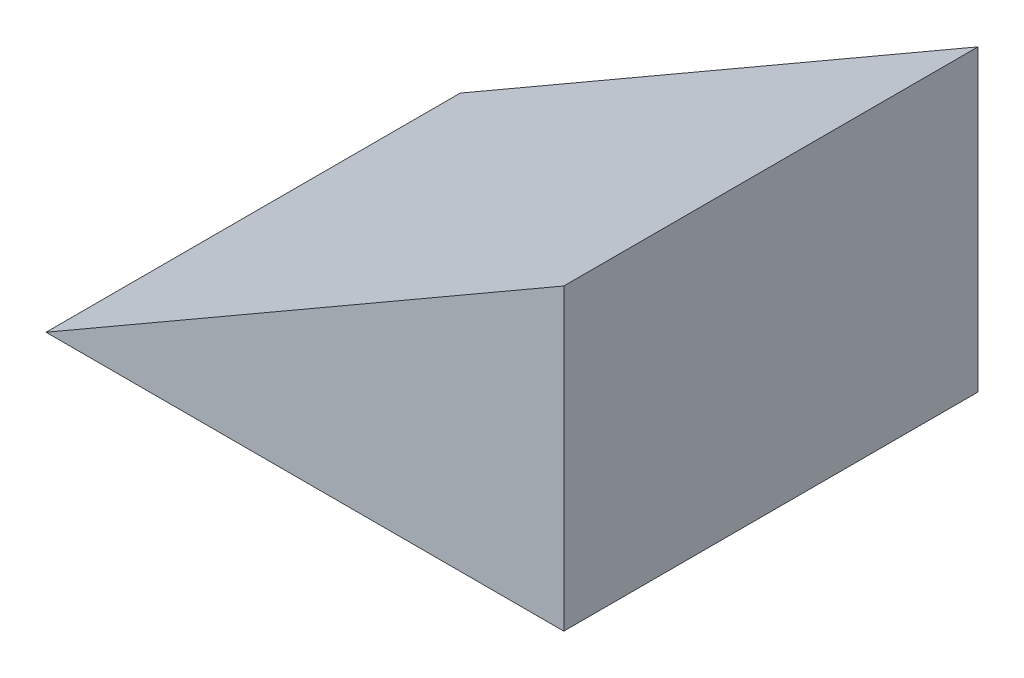
SolidWorks part; units mm, degrees
ref_plane "Front Plane" through (0, 0, 0) normal (0, 0, 1) x (1, 0, 0)
ref_plane "Top Plane" through (0, 0, 0) normal (0, 1, 0) x (1, 0, 0)
ref_plane "Right Plane" through (0, 0, 0) normal (1, 0, 0) x (0, 0, -1)
sketch "Sketch1" plane through (0, 0, 0) normal (0, 0, 1) x (1, 0, 0)
  line L0 (0, 0) -> (50, 28.8675)
  line L1 (0, 0) -> (50, 0)
  line L2 (0, 0) -> (0, 28.8675)
  line L3 (0, 28.8675) -> (50, 28.8675)
  line L4 (50, 0) -> (50, 28.8675)
  dimension "D1" = 30
  dimension "D2" = 50
extrude "Boss-Extrude1" add sketch "Sketch1" along normal blind 40 contours L1 L4 L0
